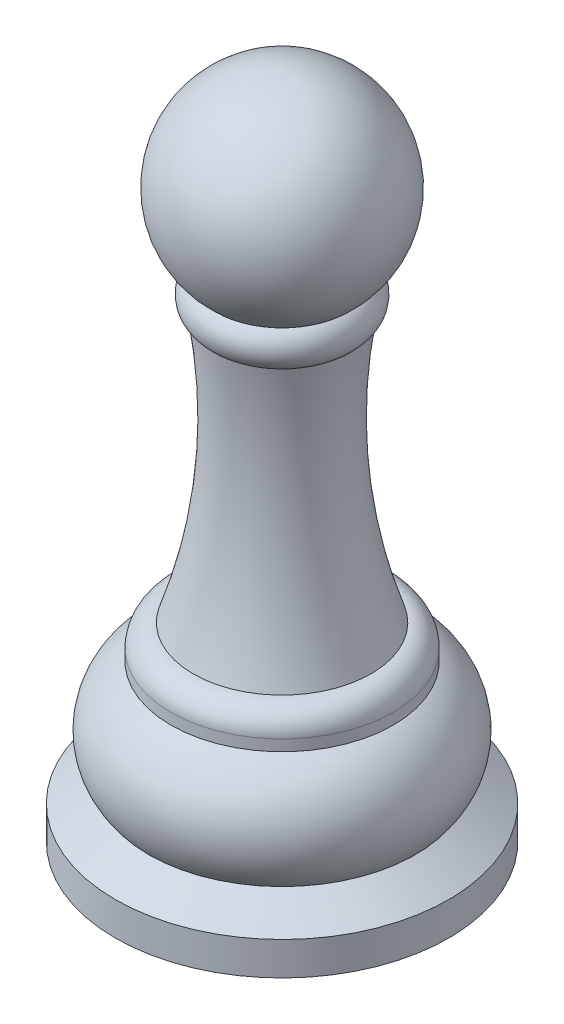
SolidWorks part; units mm, degrees
ref_plane "Front Plane" through (0, 0, 0) normal (0, 0, 1) x (1, 0, 0)
ref_plane "Top Plane" through (0, 0, 0) normal (0, 1, 0) x (1, 0, 0)
ref_plane "Right Plane" through (0, 0, 0) normal (1, 0, 0) x (0, 0, -1)
sketch "Sketch1" plane through (0, 0, 0) normal (0, 0, 1) x (1, 0, 0)
  line L0 (0, 67.8721) -> (0, -81.3701) construction
  line L7 (-10, -44.9082) -> (-10, -45.9082)
  line L9 (-12, -55) -> (-15, -57)
  line L10 (-15, -57) -> (-15, -60)
  line L11 (-15, -60) -> (0, -60)
  line L12 (0, -60) -> (0, 0)
  line L13 (-15, -57) -> (0, -57) construction
  arc A0 (0, 0) -> (-6, -15.7082) centre (0, -9) ccw
  arc A1 (-8, -42.9082) -> (-6, -18.9082) centre (-55.3607, -26.8781) ccw
  arc A2 (-6, -15.7082) -> (-6, -18.9082) centre (-4.8, -17.3082) ccw
  arc A3 (-10, -45.9082) -> (-12, -55) centre (-7.3023, -51.2675) ccw
  arc A4 (-8, -42.9082) -> (-10, -44.9082) centre (-8, -44.9082) ccw
  dimension "D1" = 9
  dimension "D13" = 50
  dimension "D14" = 6
  dimension "D2" = 2
  dimension "D16" = 6
  dimension "D17" = 24
  dimension "D10" = 2
  dimension "D3" = 3.2
  dimension "D4" = 3
  dimension "D5" = 2
  dimension "D6" = 12
  dimension "D7" = 10
  dimension "D8" = 51
  dimension "D9" = 8
  dimension "D11" = 3
  dimension "D12" = 15
  dimension "D15" = 6
revolve "Revolve1" add sketch "Sketch1" angle 360 about L0
